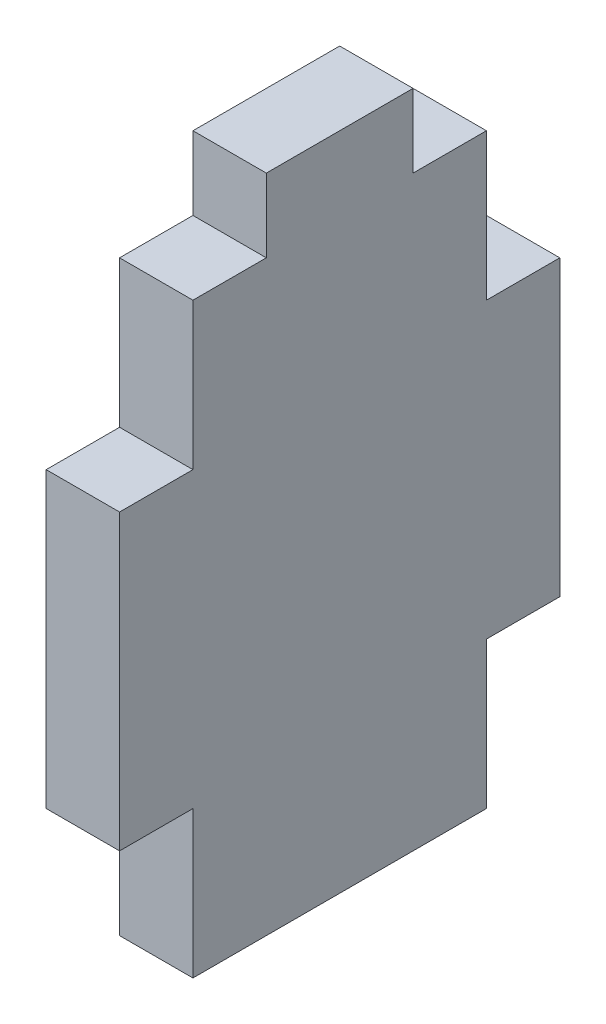
SolidWorks part; units mm, degrees
ref_plane "前视基准面" through (0, 0, 0) normal (0, 0, 1) x (1, 0, 0)
ref_plane "上视基准面" through (0, 0, 0) normal (0, 1, 0) x (1, 0, 0)
ref_plane "右视基准面" through (0, 0, 0) normal (1, 0, 0) x (0, 0, -1)
sketch "草图2" plane through (0, 0, 0) normal (1, 0, 0) x (0, 0, -1)
  line L0 (-15, 40) -> (-20, 40)
  line L1 (0, 0) -> (-20, 0)
  line L2 (0, 0) -> (0, 10)
  line L3 (0, 40) -> (-5, 40)
  line L4 (-20, 0) -> (-20, 10)
  line L5 (-20, 30) -> (-25, 30)
  line L7 (-20, 10) -> (-25, 10)
  line L8 (-25, 30) -> (-25, 10)
  line L9 (0, 30) -> (5, 30)
  line L11 (0, 10) -> (5, 10)
  line L12 (5, 30) -> (5, 10)
  line L14 (-15, 40) -> (-15, 45)
  line L15 (-15, 45) -> (-5, 45)
  line L16 (-5, 40) -> (-5, 45)
  line L17 (-20, 30) -> (-20, 40)
  line L18 (0, 30) -> (0, 40)
  dimension "D1" = 20
  dimension "D2" = 40
  dimension "D3" = 5
  dimension "D4" = 5
  dimension "D5" = 5
  dimension "D6" = 10
  dimension "D7" = 20
  dimension "D8" = 20
  dimension "D9" = 10
  dimension "D10" = 10
  dimension "D11" = 5
extrude "凸台-拉伸1" add sketch "草图2" along normal blind 5
